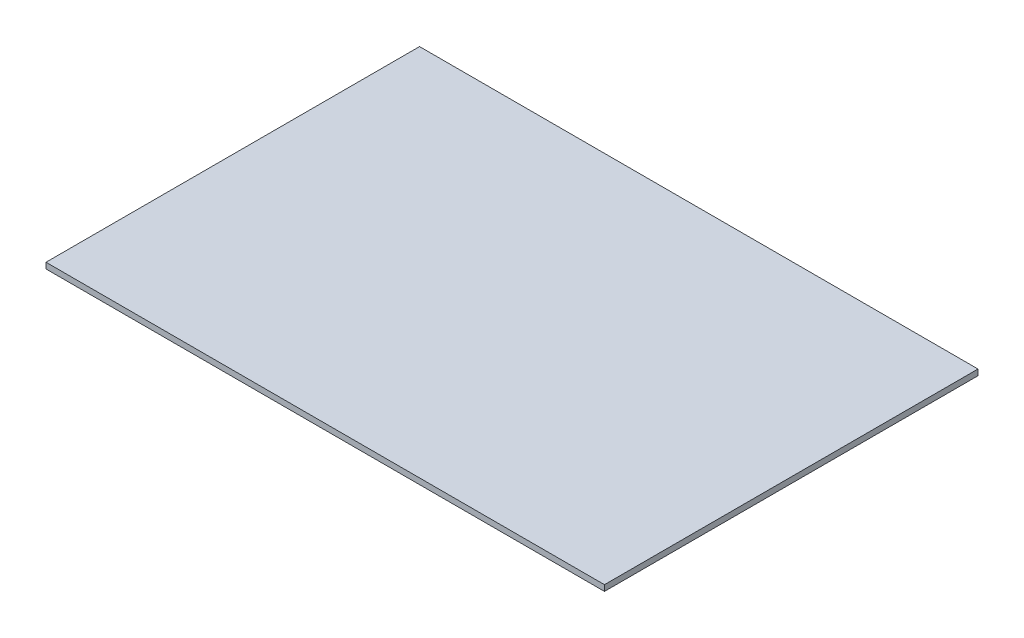
SolidWorks part; units mm, degrees
ref_plane "Front Plane" through (0, 0, 0) normal (0, 0, 1) x (1, 0, 0)
ref_plane "Top Plane" through (0, 0, 0) normal (0, 1, 0) x (1, 0, 0)
ref_plane "Right Plane" through (0, 0, 0) normal (1, 0, 0) x (0, 0, -1)
sketch "Sketch5" plane through (0, 0, 0) normal (0, 1, 0) x (1, 0, 0)
  line L1 (-76.25, -51) -> (76.25, -51)
  line L2 (-76.25, -51) -> (-76.25, 51)
  line L3 (-76.25, 51) -> (76.25, 51)
  line L4 (76.25, -51) -> (76.25, 51)
  line L5 (-76.25, -51) -> (76.25, 51) construction
  line L6 (-76.25, 51) -> (76.25, -51) construction
  point P0 (0, 0)
  dimension "D1" = 152.5
  dimension "D2" = 102
extrude "Boss-Extrude1" add sketch "Sketch5" along normal blind 1.6
